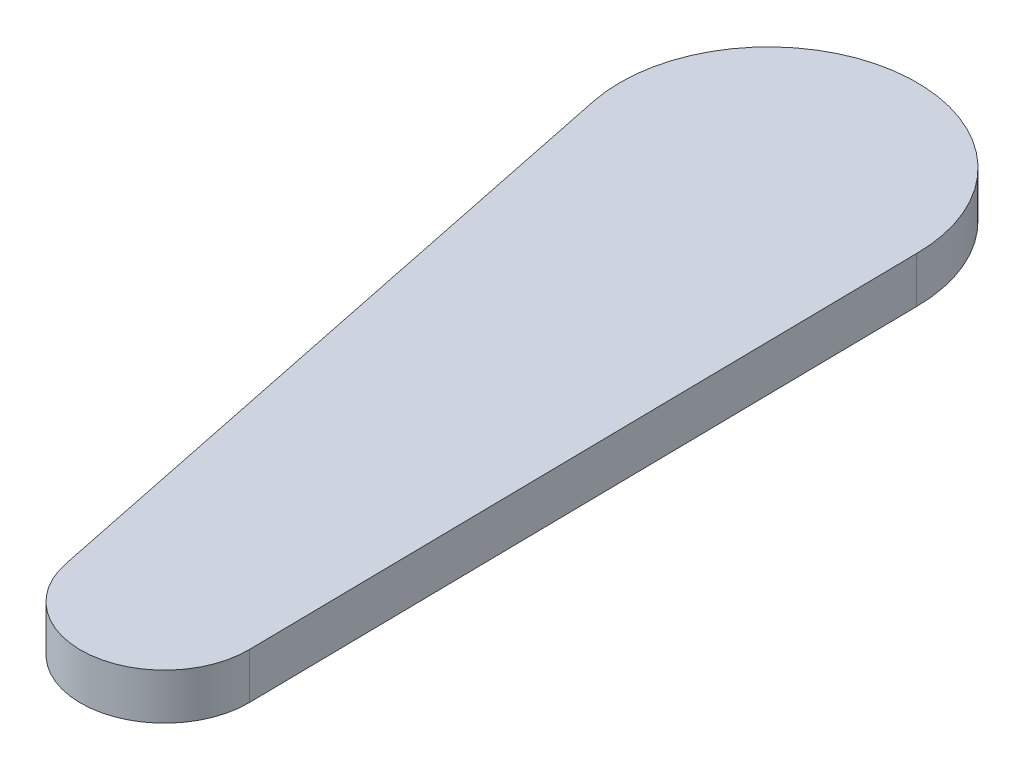
SolidWorks part; units mm, degrees
ref_plane "Płaszczyzna przednia" through (0, 0, 0) normal (0, 0, 1) x (1, 0, 0)
ref_plane "Płaszczyzna górna" through (0, 0, 0) normal (0, 1, 0) x (1, 0, 0)
ref_plane "Płaszczyzna prawa" through (0, 0, 0) normal (1, 0, 0) x (0, 0, -1)
sketch "Szkic1" plane through (0, 390.8923, 0) normal (0, 1, 0) x (1, 0, 0)
  circle A1 centre (232.3247, 1607.4361) radius 6.45
  circle A3 centre (235.5341, 1577.9361) radius 3.65
  point P0 (232.3247, 1607.4361)
  dimension "D2" = 7.3
  dimension "D3" = 12.9
  dimension "D1" = 29.5
sketch "Szkic2" plane through (0, 390.8923, 0) normal (0, 1, 0) x (1, 0, 0)
  line L1 (226.007, 1606.1365) -> (231.9589, 1577.2007)
  line L2 (239.1837, 1577.9868) -> (238.7747, 1607.4361)
  circle A0 centre (232.3247, 1607.4361) radius 6.45 construction
  arc A1 (238.7747, 1607.4361) -> (226.007, 1606.1365) centre (232.3247, 1607.4361) ccw
  circle A2 centre (235.5341, 1577.9361) radius 3.65 construction
  arc A3 (231.9589, 1577.2007) -> (239.1837, 1577.9868) centre (235.5341, 1577.9361) ccw
extrude "Dodanie-wyciągnięcie1" add sketch "Szkic2" along normal blind 2
sketch "Szkic3" plane through (0, 392.8923, 0) normal (0, 1, 0) x (1, 0, 0)
  circle A0 centre (235.5341, 1577.9361) radius 5
  arc A1 (231.9589, 1577.2007) -> (239.1837, 1577.9868) centre (235.5341, 1577.9361) ccw construction
  dimension "D1" = 0
  dimension "D2" = 10
sketch "Szkic4" plane through (0, 390.8923, 0) normal (0, -1, 0) x (1, 0, 0)
  line L0 (235.5341, -1577.9361) -> (232.3247, -1607.4361)
